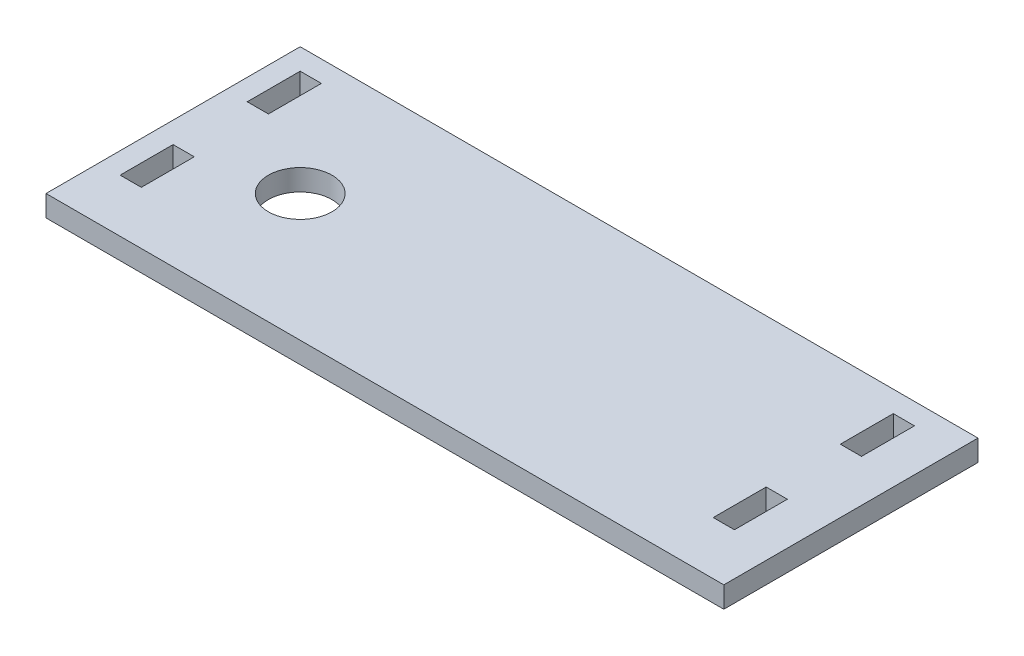
SolidWorks part; units mm, degrees
ref_plane "Front Plane" through (0, 0, 0) normal (0, 0, 1) x (1, 0, 0)
ref_plane "Top Plane" through (0, 0, 0) normal (0, 1, 0) x (1, 0, 0)
ref_plane "Right Plane" through (0, 0, 0) normal (1, 0, 0) x (0, 0, -1)
sketch "Sketch1" plane through (0, 0, 0) normal (0, 1, 0) x (1, 0, 0)
  line L0 (-95.25, -6.35) -> (-88.9, -6.35)
  line L1 (-101.6, 38.1) -> (101.6, 38.1)
  line L2 (-101.6, 38.1) -> (-101.6, -38.1)
  line L3 (-101.6, -38.1) -> (101.6, -38.1)
  line L4 (101.6, 38.1) -> (101.6, -38.1)
  line L5 (-95.25, 31.75) -> (-88.9, 31.75)
  line L6 (-95.25, 31.75) -> (-95.25, 15.875)
  line L7 (-95.25, 15.875) -> (-88.9, 15.875)
  line L8 (-88.9, 31.75) -> (-88.9, 15.875)
  line L9 (-95.25, -6.35) -> (-95.25, -22.225)
  line L10 (-95.25, -22.225) -> (-88.9, -22.225)
  line L11 (-88.9, -6.35) -> (-88.9, -22.225)
  line L13 (82.55, 31.75) -> (88.9, 31.75)
  line L14 (82.55, 31.75) -> (82.55, 15.875)
  line L15 (82.55, 15.875) -> (88.9, 15.875)
  line L16 (88.9, 31.75) -> (88.9, 15.875)
  line L17 (82.55, -6.35) -> (88.9, -6.35)
  line L18 (82.55, -6.35) -> (82.55, -22.225)
  line L19 (82.55, -22.225) -> (88.9, -22.225)
  line L20 (88.9, -6.35) -> (88.9, -22.225)
  circle A0 centre (-63.5, 0) radius 9.525
  point P7 (-101.6, 0)
  point P13 (0, 38.1)
  point P18 (-92.075, -22.225)
  point P26 (85.725, 31.75)
  dimension "D1" = 19.05
  dimension "D2" = 6.35
  dimension "D3" = 38.1
  dimension "D4" = 165.1
  dimension "D5" = 6.35
  dimension "D6" = 15.875
  dimension "D7" = 6.35
  dimension "D8" = 38.1
  dimension "D9" = 22.225
  dimension "D10" = 171.45
extrude "Boss-Extrude1" add sketch "Sketch1" along normal blind 6.35
